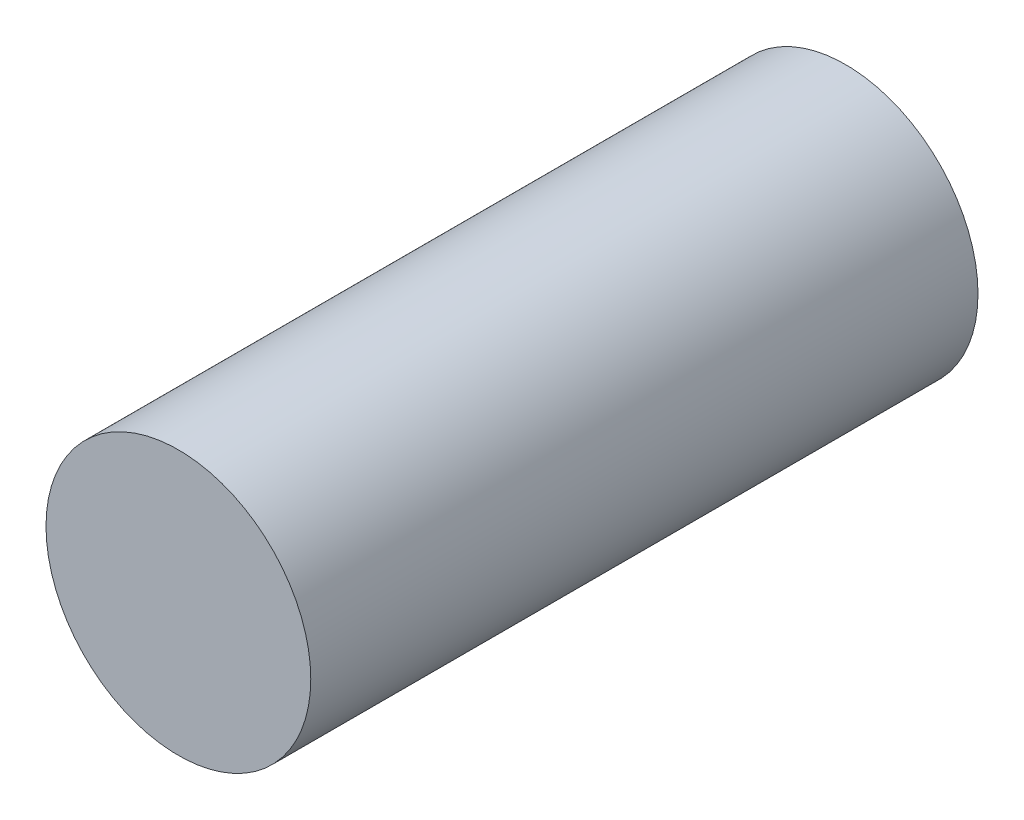
SolidWorks part; units mm, degrees
ref_plane "Front Plane" through (0, 0, 0) normal (0, 0, 1) x (1, 0, 0)
ref_plane "Top Plane" through (0, 0, 0) normal (0, 1, 0) x (1, 0, 0)
ref_plane "Right Plane" through (0, 0, 0) normal (1, 0, 0) x (0, 0, -1)
sketch "Sketch1" plane through (0, 0, 0) normal (0, 0, 1) x (1, 0, 0)
  circle A1 centre (5.4357, 11.9602) radius 0.25
extrude "Boss-Extrude1" add sketch "Sketch1" along normal blind 1.26
